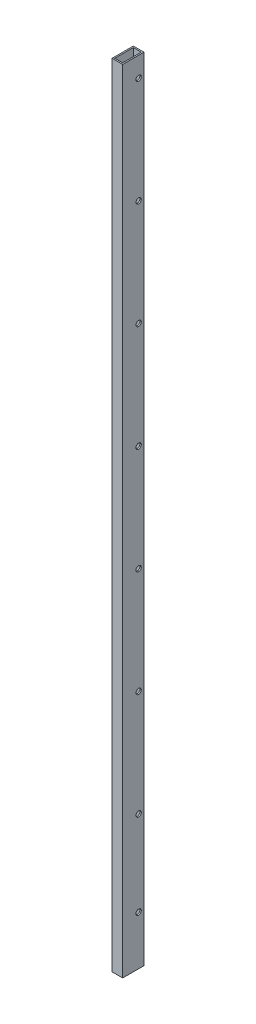
SolidWorks part; units mm, degrees
ref_plane "Front Plane" through (0, 0, 0) normal (0, 0, 1) x (1, 0, 0)
ref_plane "Top Plane" through (0, 0, 0) normal (0, 1, 0) x (1, 0, 0)
ref_plane "Right Plane" through (0, 0, 0) normal (1, 0, 0) x (0, 0, -1)
sketch "Sketch1" plane through (0, 0, 0) normal (0, 1, 0) x (1, 0, 0)
  line L0 (-9.525, -22.225) -> (9.525, -22.225)
  line L1 (-12.7, 25.4) -> (12.7, 25.4)
  line L2 (-12.7, 25.4) -> (-12.7, -25.4)
  line L3 (-12.7, -25.4) -> (12.7, -25.4)
  line L4 (12.7, 25.4) -> (12.7, -25.4)
  line L5 (-12.7, 25.4) -> (12.7, -25.4) construction
  line L6 (-12.7, -25.4) -> (12.7, 25.4) construction
  line L7 (9.525, 22.225) -> (9.525, -22.225)
  line L8 (-9.525, 22.225) -> (9.525, 22.225)
  line L9 (-9.525, 22.225) -> (-9.525, -22.225)
  point P0 (0, 0)
  dimension "D1" = 50.8
  dimension "D2" = 25.4
  dimension "D3" = 3.175
extrude "Boss-Extrude2" add sketch "Sketch1" along normal blind 1892.3
sketch "Sketch2" plane through (12.7, 0, 0) normal (1, 0, 0) x (0, 0, -1)
  circle A0 centre (12.7, 1844.6586) radius 3.175
  circle A1 centre (12.7, 1590.6586) radius 3.175
  circle A2 centre (12.7, 1336.6586) radius 3.175
  circle A3 centre (12.7, 1082.6586) radius 3.175
  circle A4 centre (12.7, 828.6586) radius 3.175
  circle A5 centre (12.7, 574.6586) radius 3.175
  circle A6 centre (12.7, 320.6586) radius 3.175
  dimension "D1" = 7
extrude "Cut-Extrude1" cut sketch "Sketch2" against normal blind 25.4
sketch "Sketch3" plane through (12.7, 0, 0) normal (1, 0, 0) x (0, 0, -1)
  circle A0 centre (12.7, 117.4586) radius 3.175
extrude "Cut-Extrude2" cut sketch "Sketch3" against normal blind 25.4
sketch "Sketch4" plane through (12.7, 0, 0) normal (1, 0, 0) x (0, 0, -1)
  circle A0 centre (12.7, 1844.6586) radius 6.35
  circle A1 centre (12.7, 1590.6586) radius 6.35
  circle A2 centre (12.7, 1336.6586) radius 6.35
  circle A3 centre (12.7, 1082.6586) radius 6.35
  circle A4 centre (12.7, 828.6586) radius 6.35
  circle A5 centre (12.7, 574.6586) radius 6.35
  circle A6 centre (12.7, 320.6586) radius 6.35
  dimension "D1" = 12.7
  dimension "D2" = 7
extrude "Cut-Extrude3" cut sketch "Sketch4" against normal blind 3.175
sketch "Sketch5" plane through (12.7, 0, 0) normal (1, 0, 0) x (0, 0, -1)
  circle A0 centre (12.7, 117.4586) radius 6.35
extrude "Cut-Extrude4" cut sketch "Sketch5" against normal blind 3.175
